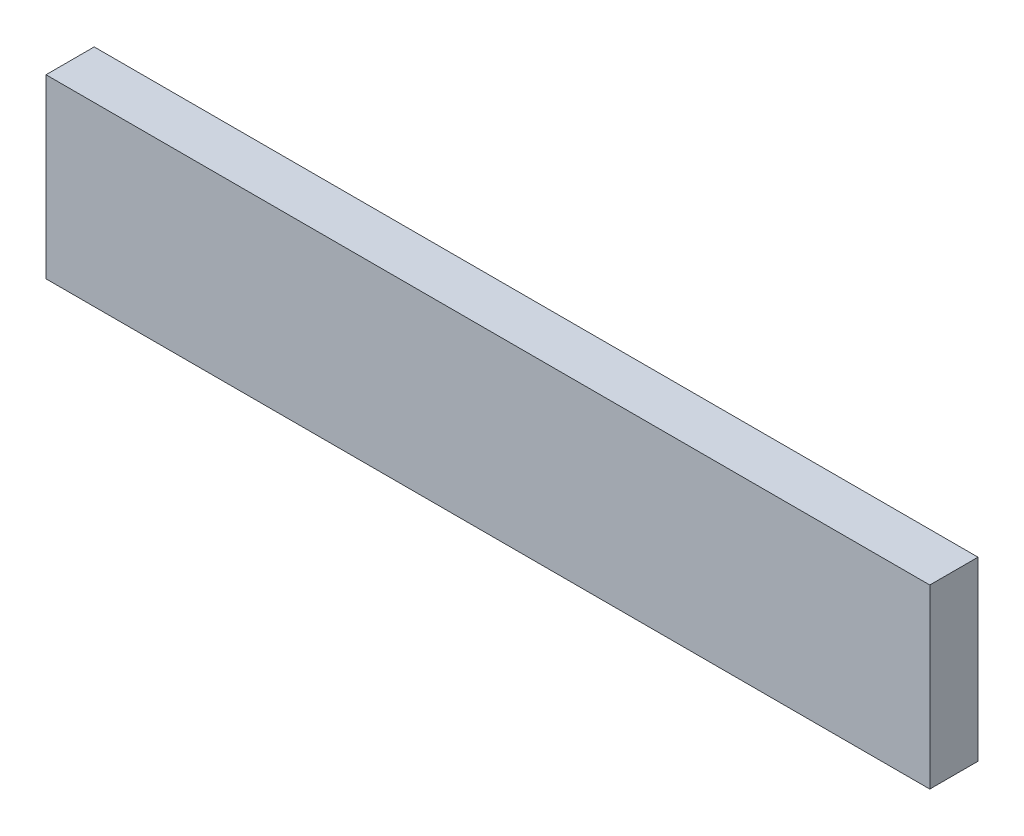
SolidWorks part; units mm, degrees
ref_plane "Front Plane" through (0, 0, 0) normal (0, 0, 1) x (1, 0, 0)
ref_plane "Top Plane" through (0, 0, 0) normal (0, 1, 0) x (1, 0, 0)
ref_plane "Right Plane" through (0, 0, 0) normal (1, 0, 0) x (0, 0, -1)
sketch "Sketch1" plane through (0, 0, 0) normal (0, 0, 1) x (1, 0, 0)
  line L1 (0, 0) -> (55, 0)
  line L2 (0, 0) -> (0, 11)
  line L3 (0, 11) -> (55, 11)
  line L4 (55, 0) -> (55, 11)
  dimension "D1" = 55
  dimension "D2" = 11
extrude "Boss-Extrude1" add sketch "Sketch1" along normal blind 3
